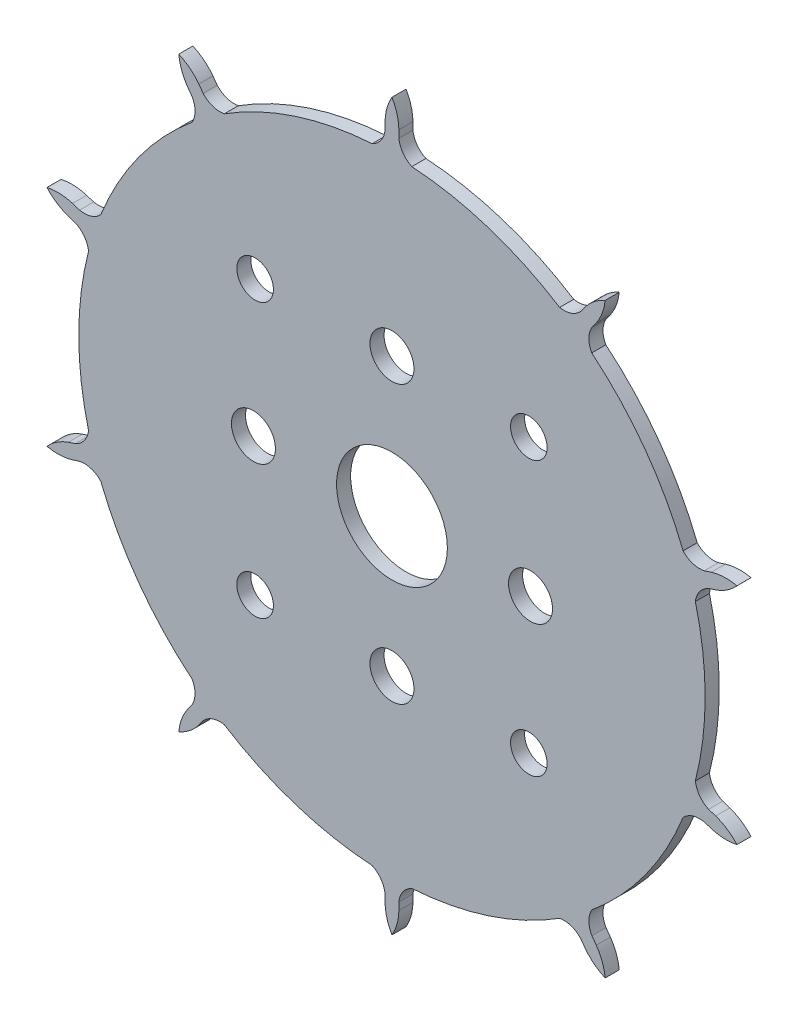
SolidWorks part; units mm, degrees
ref_plane "Front Plane" through (0, 0, 0) normal (0, 0, 1) x (1, 0, 0)
ref_plane "Top Plane" through (0, 0, 0) normal (0, 1, 0) x (1, 0, 0)
ref_plane "Right Plane" through (0, 0, 0) normal (1, 0, 0) x (0, 0, -1)
sketch "Sketch1" plane through (0, 0, 0) normal (0, 0, 1) x (1, 0, 0)
  circle A0 centre (0, 10) radius 1.5875
  circle A1 centre (0, 0) radius 22.6042
  circle A2 centre (9.8783, -9.8783) radius 1.3208
  circle A3 centre (9.8783, 9.8783) radius 1.3208
  circle A4 centre (-9.8783, -9.8783) radius 1.3208
  circle A5 centre (-9.8783, 9.8783) radius 1.3208
  circle A6 centre (0, 0) radius 4
  circle A7 centre (10, 0) radius 1.5875
  circle A8 centre (0, -10) radius 1.5875
  circle A9 centre (-10, 0) radius 1.5875
  dimension "D1" = 4
  dimension "D2" = 4
extrude "Boss-Extrude2" add sketch "Sketch1" along normal blind 1.016
sketch "Sketch2" plane through (0, 0, 1.016) normal (0, 0, 1) x (1, 0, 0)
  line L0 (-0.5, 23.868) -> (-0.5, 24.4014)
  line L1 (0.5, 23.868) -> (0.5, 24.4014)
  arc A0 (0.5, 24.4014) -> (0, 26.1794) centre (-3.159, 24.3318) ccw
  arc A1 (-0.5, 23.868) -> (-1.6391, 22.4794) centre (-2.1172, 24.0331) cw
  arc A2 (-0.5, 24.4014) -> (0, 26.1794) centre (3.159, 24.3318) cw
  arc A3 (0.5, 23.868) -> (1.6391, 22.4794) centre (2.1172, 24.0331) ccw
  arc A4 (-1.6391, 22.4794) -> (1.6391, 22.4794) centre (0, 28.2138) ccw
extrude "Boss-Extrude4" add sketch "Sketch2" against normal blind 1.016
pattern_circular "CirPattern1" count 10 every 36 about axis through (0, 0, 0) along (0, 0, 1) of "Boss-Extrude4"
